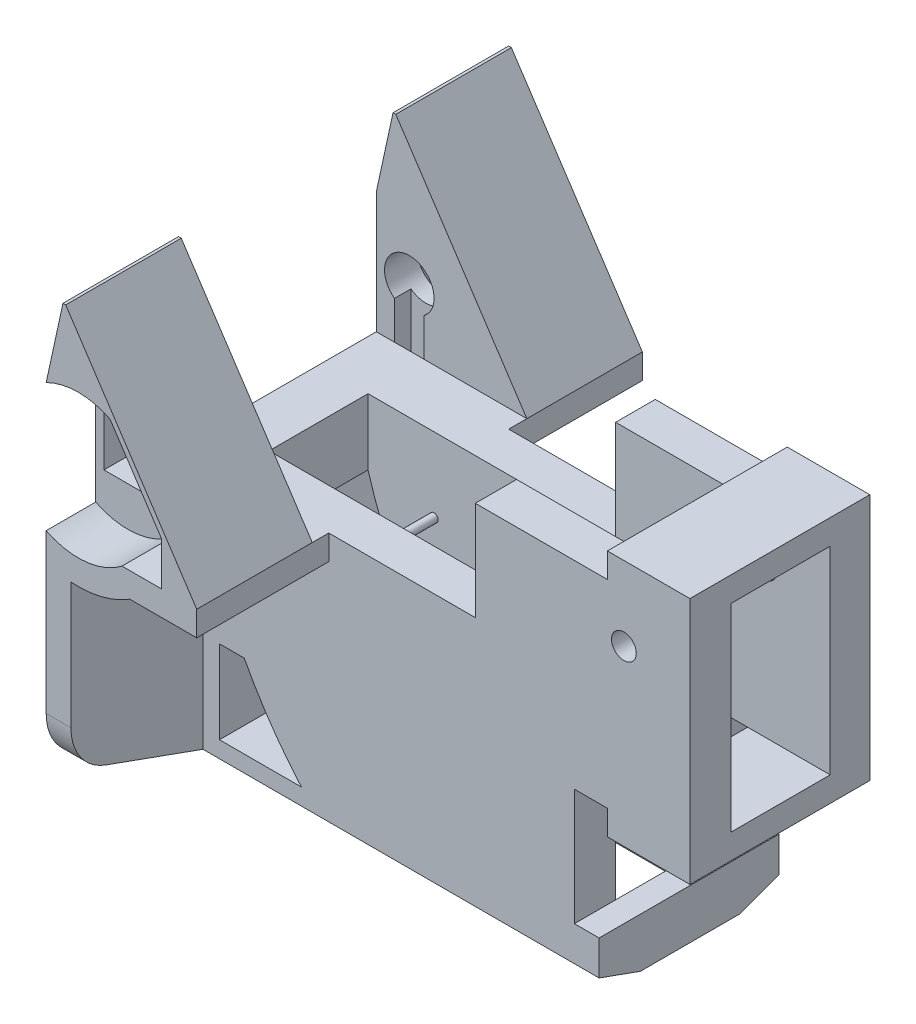
SolidWorks part; units mm, degrees
ref_plane "前视基准面" through (0, 0, 0) normal (0, 0, 1) x (1, 0, 0)
ref_plane "上视基准面" through (0, 0, 0) normal (0, 1, 0) x (1, 0, 0)
ref_plane "右视基准面" through (0, 0, 0) normal (1, 0, 0) x (0, 0, -1)
sketch "草图1" plane through (0, 0, 0) normal (1, 0, 0) x (0, 0, -1)
  line L0 (135, 0) -> (135, -170) construction
  line L1 (0, 0) -> (270, 0)
  line L2 (0, 0) -> (0, -100.2828)
  line L4 (270, 0) -> (270, -100.2828)
  line L5 (38.49, -136.6392) -> (62.3511, -70.3586) construction
  line L6 (21.17, -130.404) -> (127.5448, -168.6989) construction
  line L7 (142.4552, -168.6989) -> (248.83, -130.404) construction
  line L8 (58.2053, -81.8746) -> (-5.8219, -81.8746) construction
  line L9 (58.2053, -81.8746) -> (5.8219, -118.6911) construction
  line L10 (127.5448, -168.6989) -> (21.17, -130.404)
  line L11 (142.4552, -168.6989) -> (248.83, -130.404)
  line L12 (105.5031, -160.7639) -> (135, -78.8281) construction
  line L13 (135, -78.8281) -> (164.4969, -160.7639) construction
  arc A0 (0, -100.2828) -> (21.17, -130.404) centre (32.0136, -100.2828) ccw
  arc A1 (127.5448, -168.6989) -> (142.4552, -168.6989) centre (135, -147.9899) ccw
  arc A2 (270, -100.2828) -> (248.83, -130.404) centre (237.9864, -100.2828) cw
  dimension "D2" = 44.0202
  dimension "D3" = 170
  dimension "D1" = 270
  dimension "D4" = 32.0136
  dimension "D5" = 109.799
  dimension "D6" = 109.799
extrude "凸台-拉伸1" add sketch "草图1" along normal blind 30
sketch "草图2" plane through (30, 0, 0) normal (1, 0, 0) x (0, 0, -1)
  line L0 (135, 0) -> (135, -170) construction
  line L1 (270, 0) -> (0, 0) construction
  line L2 (135, -14.9009) -> (165, -14.9009) construction
  line L3 (165, 0) -> (165, -160.5828)
  line L4 (105, 0) -> (105, -160.5828)
  line L8 (0, 0) -> (0, -100.2828)
  line L9 (21.17, -130.404) -> (127.5448, -168.6989)
  line L10 (142.4552, -168.6989) -> (248.83, -130.404)
  line L11 (270, -100.2828) -> (270, 0)
  line L12 (270, 0) -> (0, 0)
  line L13 (0, 0) -> (0, -100.2828)
  line L14 (21.17, -130.404) -> (127.5448, -168.6989)
  line L15 (142.4552, -168.6989) -> (248.83, -130.404)
  line L16 (270, -100.2828) -> (270, 0)
  line L17 (270, 0) -> (0, 0)
  arc A0 (127.5448, -168.6989) -> (142.4552, -168.6989) centre (135, -147.9899) ccw construction
  arc A4 (0, -100.2828) -> (21.17, -130.404) centre (32.0136, -100.2828) ccw
  arc A5 (127.5448, -168.6989) -> (142.4552, -168.6989) centre (135, -147.9899) ccw
  arc A6 (248.83, -130.404) -> (270, -100.2828) centre (237.9864, -100.2828) ccw
  arc A7 (0, -100.2828) -> (21.17, -130.404) centre (32.0136, -100.2828) ccw
  arc A8 (127.5448, -168.6989) -> (142.4552, -168.6989) centre (135, -147.9899) ccw
  arc A9 (248.83, -130.404) -> (270, -100.2828) centre (237.9864, -100.2828) ccw
  line M12 (0, 0) -> (0, -100.2828)
  arc M13 (0, -100.2828) -> (21.17, -130.404) centre (32.0136, -100.2828) ccw
  line M14 (21.17, -130.404) -> (127.5448, -168.6989)
  line M16 (142.4552, -168.6989) -> (248.83, -130.404)
  arc M17 (248.83, -130.404) -> (270, -100.2828) centre (237.9864, -100.2828) ccw
  line M18 (270, -100.2828) -> (270, 0)
  line M19 (270, 0) -> (0, 0)
  dimension "D1" = 30
  dimension "D2" = 0
extrude "凸台-拉伸2" add sketch "草图2" along normal blind 210 contours L4 M19 M12 M13 M14 | L3 M19 M16 M17 M18
sketch "草图6" plane through (0, 0, -105) normal (0, 0, -1) x (-1, 0, 0)
  line L0 (-71.1167, 0) -> (-71.1167, -409.9146) construction
  line L8 (-30, -160.5828) -> (-30, 0)
  line L9 (-30, 0) -> (-240, 0)
  line L12 (-240, 0) -> (-240, -160.5828)
  line L13 (-240, -160.5828) -> (-30, -160.5828)
  line L15 (-30, -160.5828) -> (-30, 0)
  line L16 (-30, 0) -> (-240, 0)
  line L19 (-240, 0) -> (-240, -160.5828)
  line L20 (-240, -160.5828) -> (-30, -160.5828)
  dimension "D2" = 41.1167
  dimension "D1" = 0
sketch "草图8" plane through (240, 0, 0) normal (1, 0, 0) x (0, 0, -1)
  line L0 (105, 0) -> (105, -160.5828) construction
  line L1 (105, -60) -> (80, -60)
  line L2 (105, -60) -> (105, 60)
  line L3 (105, 60) -> (80, 60)
  line L4 (80, -60) -> (80, 60)
  line L5 (105, -60) -> (80, 60) construction
  line L6 (105, 60) -> (80, -60) construction
  line L7 (135, 0) -> (135, -208.0575) construction
  line L8 (165, 0) -> (105, 0) construction
  line L9 (105, 0) -> (0, 0) construction
  line L10 (165, 60) -> (190, -60) construction
  line L11 (165, -60) -> (190, 60) construction
  line L12 (190, -60) -> (190, 60)
  line L13 (165, 60) -> (190, 60)
  line L14 (165, -60) -> (165, 60)
  line L15 (165, -60) -> (190, -60)
  point P4 (92.5, 0)
  point P17 (177.5, 0)
  dimension "D1" = 25
  dimension "D2" = 60
  dimension "D3" = 60
extrude "凸台-拉伸5" add sketch "草图8" along normal blind 70
sketch "草图9" plane through (240, 0, 0) normal (-1, 0, 0) x (0, 0, 1)
  line L4 (-105, 60) -> (-105, 0)
  line L5 (-105, 0) -> (-80, 0)
  line L6 (-80, 0) -> (-80, 60)
  line L7 (-80, 60) -> (-105, 60)
  line L8 (-105, 60) -> (-105, 0)
  line L9 (-105, 0) -> (-80, 0)
  line L10 (-80, 0) -> (-80, 60)
  line L11 (-80, 60) -> (-105, 60)
  line L12 (-190, 0) -> (-165, 0)
  line L13 (-165, 0) -> (-165, 60)
  line L14 (-165, 60) -> (-190, 60)
  line L15 (-190, 60) -> (-190, 0)
  line L16 (-190, 0) -> (-165, 0)
  line L17 (-165, 0) -> (-165, 60)
  line L18 (-165, 60) -> (-190, 60)
  line L19 (-190, 60) -> (-190, 0)
  dimension "D1" = 0
  dimension "D2" = 0
extrude "凸台-拉伸6" add sketch "草图9" along normal blind 60
sketch "草图10" plane through (0, 0, -80) normal (0, 0, 1) x (1, 0, 0)
  line L0 (240, 0) -> (240, 31.0013) construction
  line L2 (180, 30) -> (270, 30) construction
  line L3 (180, 0) -> (180, 60) construction
  circle A0 centre (270, 30) radius 7.5
  dimension "D2" = 15
  dimension "D1" = 30
extrude "切除-拉伸3" cut sketch "草图10" against normal through all
sketch "草图11" plane through (0, 0, -105) normal (0, 0, -1) x (-1, 0, 0)
  line L0 (0, 0) -> (0, 80.2418) construction
  line L1 (-240, -160.5828) -> (-124.1295, -160.5828) construction
  line L2 (-124.1295, -160.5828) -> (-108.2032, -160.5828) construction
  line L3 (-30, 0) -> (-30, -40) construction
  line L4 (-30, -40) -> (-30, -160.5828)
  line L5 (-30, -160.5828) -> (-108.2032, -160.5828)
  circle A0 centre (-270, 30) radius 240 construction
  arc A1 (-108.2032, -160.5828) -> (-30, -40) centre (-270, 30) ccw
  circle A2 centre (-270, 30) radius 250 construction
  dimension "D1" = 480
  dimension "D2" = 10
extrude "凸台-拉伸7" add sketch "草图11" along normal blind 60
sketch "草图12" plane through (0, 0, -165) normal (0, 0, 1) x (1, 0, 0)
  line L0 (30, 0) -> (240, 0) construction
  line L1 (70, -45) -> (70, 0) construction
  line L4 (30, -160.5828) -> (30, 0) construction
  circle A0 centre (70, -45) radius 2.5
  dimension "D3" = 5
  dimension "D4" = 45
  dimension "D1" = 45
  dimension "D2" = 40
extrude "凸台-拉伸8" add sketch "草图12" along normal through all
sketch "草图13" plane through (0, 0, 0) normal (0, 1, 0) x (1, 0, 0)
  line L0 (0, 270) -> (0, 240.5719) construction
  line L1 (0, 270) -> (0, 0) construction
  line L2 (0, 240.5719) -> (0, 192.1942) construction
sketch "草图14" plane through (0, 0, 0) normal (0, 1, 0) x (1, 0, 0)
  line L0 (0, 250) -> (0, 200)
  line L1 (0, 250) -> (125, 250)
  line L2 (0, 200) -> (125, 200)
  line L3 (125, 250) -> (125, 200)
  line L4 (0, 270) -> (0, 0) construction
  line L5 (240, 270) -> (0, 270) construction
  line L6 (0, 135) -> (52.375, 135) construction
  line L7 (125, 20) -> (125, 70)
  line L8 (0, 70) -> (125, 70)
  line L9 (0, 20) -> (125, 20)
  line L10 (0, 20) -> (0, 70)
  dimension "D1" = 20
  dimension "D2" = 50
  dimension "D3" = 125
extrude "凸台-拉伸9" add sketch "草图14" along normal blind 120
sketch "草图15" plane through (0, 0, -20) normal (0, 0, 1) x (1, 0, 0)
  line L0 (0, 120) -> (0, 0) construction
  line L1 (0, 70) -> (70, 70)
  line L2 (0, 70) -> (0, 0)
  line L3 (0, 0) -> (70, 0)
  line L4 (70, 70) -> (70, 0)
  line L5 (0, 120) -> (125, 120) construction
  dimension "D1" = 70
  dimension "D2" = 70
  dimension "D3" = 50
extrude "切除-拉伸4" cut sketch "草图15" against normal blind 10
sketch "草图16" plane through (0, 0, -30) normal (0, 0, 1) x (1, 0, 0)
  line L0 (0, 35) -> (70, 35) construction
  line L1 (0, 70) -> (0, 0) construction
  line L2 (70, 0) -> (70, 70) construction
  line L3 (0, 35) -> (35, 35) construction
  line L4 (35, 70) -> (35, 0) construction
  line L5 (35, 35) -> (35, 15)
  line L6 (70, 70) -> (0, 70) construction
  line L7 (0, 35) -> (35, 35) construction
  line L8 (0, 0) -> (70, 0) construction
  line L9 (35, 35) -> (35, 55) construction
  line L10 (35, 55) -> (5, 55) construction
  line L11 (35, 35) -> (35, 55)
  line L12 (35, 55) -> (5, 55)
  line L13 (5, 55) -> (5, 15)
  line L14 (35, 15) -> (5, 15)
  point P21 (5, 35)
  dimension "D1" = 35
  dimension "D2" = 20
  dimension "D3" = 30
extrude "切除-拉伸5" cut sketch "草图16" against normal blind 20 contours L14 L5 L11 L12 L13
sketch "草图17" plane through (0, 0, -30) normal (0, 0, 1) x (1, 0, 0)
  line L0 (35, 35) -> (19.5, 34.5) construction
  line L1 (35, 55) -> (35, 15) construction
  circle A0 centre (19.5, 34.5) radius 43.4713
extrude "切除-拉伸6" cut sketch "草图17" along normal through all
sketch "草图18" plane through (0, 0, -20) normal (0, 0, 1) x (1, 0, 0)
  line L0 (0, 73.3523) -> (11.8199, 120) construction
  line L1 (0, 73.3523) -> (0, -4.3523) construction
  line L2 (0, 120) -> (125, 120) construction
  line L3 (11.8199, 120) -> (62.5, 43.3973) construction
  line L4 (62.5, 43.3973) -> (91.2115, 0) construction
  line L5 (11.8199, 120) -> (91.2115, 0)
  line L6 (91.2115, 0) -> (87.3179, 0)
  line L7 (70, 0) -> (125, 0) construction
  line L8 (87.3179, 0) -> (10.7417, 115.7446)
  line L9 (10.7417, 115.7446) -> (11.8199, 120)
  arc A0 (44.5899, 70) -> (0, 73.3523) centre (19.5, 34.5) ccw construction
extrude "凸台-拉伸10" add sketch "草图18" along normal blind 20
sketch "草图19" plane through (0, 0, -20) normal (0, 0, 1) x (1, 0, 0)
  line L0 (10.856, 115.5717) -> (11.8199, 120)
  line L1 (10.7417, 115.7446) -> (87.3179, 0) construction
  line L2 (11.8199, 120) -> (10.7417, 115.7446) construction
  line L3 (11.8199, 120) -> (125, 120) construction
  line L4 (11.8199, 120) -> (0, 65.6972)
  line L5 (0, 73.3523) -> (0, -4.3523) construction
  line L6 (0, 65.6972) -> (0, 73.3523)
  line L7 (0, 120) -> (0, 73.3523) construction
  line L8 (0, 73.3523) -> (10.1537, 120)
  line L9 (0, 120) -> (11.8199, 120) construction
  line L10 (10.1537, 120) -> (11.8199, 120)
  line L11 (10.1537, 120) -> (11.8199, 120)
  line M2 (38.6846, 73.509) -> (10.7417, 115.7446)
  line M3 (10.7417, 115.7446) -> (11.8199, 120)
  line M4 (11.8199, 120) -> (0, 120)
  arc M6 (0, 73.3523) -> (38.6846, 73.509) centre (19.5, 34.5) cw
extrude "凸台-拉伸11" add sketch "草图19" along normal blind 20 contours L8 L4 M6 M2 M3 M4
sketch "草图20" plane through (0, 0, -20) normal (0, 0, 1) x (1, 0, 0)
  line L3 (0, 120) -> (0, 73.3523)
  line L4 (0, 73.3523) -> (10.1537, 120)
  line L5 (10.1537, 120) -> (0, 120)
  line L6 (0, 120) -> (0, 73.3523)
  line L7 (0, 73.3523) -> (10.1537, 120)
  line L8 (10.1537, 120) -> (0, 120)
  dimension "D1" = 0
extrude "切除-拉伸7" cut sketch "草图20" against normal through all
sketch "草图22" plane through (0, 0, -20) normal (0, 0, 1) x (1, 0, 0)
  line L0 (44.8997, 70) -> (70, 32.0611)
  line L7 (70, 32.0611) -> (91.2115, 0)
  line L8 (91.2115, 0) -> (125, 0)
  line L9 (125, 0) -> (125, 120)
  line L10 (125, 120) -> (11.8199, 120)
  line L11 (11.8199, 120) -> (44.8997, 70)
  line L12 (44.8997, 70) -> (70, 70)
  line L13 (70, 70) -> (70, 32.0611)
  line L14 (70, 32.0611) -> (91.2115, 0)
  line L15 (91.2115, 0) -> (125, 0)
  line L16 (125, 0) -> (125, 120)
  line L17 (125, 120) -> (11.8199, 120)
  line L18 (11.8199, 120) -> (44.8997, 70)
  dimension "D1" = 0
extrude "切除-拉伸8" cut sketch "草图22" against normal through all
sketch "草图23" plane through (0, 0, 0) normal (0, 0, 1) x (1, 0, 0)
  line L0 (87.3179, 0) -> (91.2115, 0)
  line L10 (0, -4.3523) -> (0, -100.2828)
  line L11 (0, -100.2828) -> (240, -100.2828)
  line L12 (240, -100.2828) -> (240, 0)
  line L13 (240, 0) -> (91.2115, 0)
  line L14 (91.2115, 0) -> (11.8199, 120)
  line L15 (11.8199, 120) -> (10.1537, 120)
  line L16 (10.1537, 120) -> (0, 73.3523)
  line L17 (1.8573, 74.2302) -> (10.856, 115.5717)
  line L18 (10.856, 115.5717) -> (87.3179, 0)
  line L19 (87.3179, 0) -> (45.9481, 0)
  line L20 (0, -4.3523) -> (0, -100.2828)
  line L21 (0, -100.2828) -> (240, -100.2828)
  line L22 (240, -100.2828) -> (240, 0)
  line L23 (240, 0) -> (91.2115, 0)
  line L24 (91.2115, 0) -> (11.8199, 120)
  line L25 (11.8199, 120) -> (10.1537, 120)
  line L26 (10.1537, 120) -> (0, 73.3523)
  line L27 (1.8573, 74.2302) -> (10.856, 115.5717)
  line L28 (10.856, 115.5717) -> (87.3179, 0)
  line L29 (87.3179, 0) -> (45.9481, 0)
  arc A2 (0, -4.3523) -> (45.9481, 0) centre (19.5, 34.5) ccw
  arc A3 (1.8573, 74.2302) -> (0, 73.3523) centre (19.5, 34.5) ccw
  arc A4 (0, -4.3523) -> (45.9481, 0) centre (19.5, 34.5) ccw
  arc A5 (1.8573, 74.2302) -> (0, 73.3523) centre (19.5, 34.5) ccw
  line M18 (91.2115, 0) -> (11.8199, 120)
  line M19 (11.8199, 120) -> (10.1537, 120)
  line M20 (10.1537, 120) -> (0, 73.3523)
  arc M21 (0, 73.3523) -> (1.8573, 74.2302) centre (19.5, 34.5) cw
  line M22 (1.8573, 74.2302) -> (10.856, 115.5717)
  line M23 (10.856, 115.5717) -> (87.3179, 0)
  dimension "D1" = 0
extrude "凸台-拉伸19" add sketch "草图23" against normal up to next contours L0 M23 M18 M19 M20 M21 M22
sketch "草图24" plane through (0, 0, -20) normal (0, 0, 1) x (1, 0, 0)
  line L3 (87.3179, 0) -> (70, 26.1759)
  line L4 (70, 26.1759) -> (70, 0)
  line L5 (70, 0) -> (87.3179, 0)
  line L6 (87.3179, 0) -> (70, 26.1759)
  line L7 (70, 26.1759) -> (70, 0)
  line L8 (70, 0) -> (87.3179, 0)
  dimension "D1" = 0
extrude "凸台-拉伸20" add sketch "草图24" along normal up to vertex (20 mm away)
sketch "草图25" plane through (0, 0, -20) normal (0, 0, 1) x (1, 0, 0)
  line L2 (38.6846, 73.509) -> (10.856, 115.5717)
  line L3 (10.856, 115.5717) -> (1.8573, 74.2302)
  line L4 (38.6846, 73.509) -> (10.856, 115.5717)
  line L5 (10.856, 115.5717) -> (1.8573, 74.2302)
  arc A1 (38.6846, 73.509) -> (1.8573, 74.2302) centre (19.5, 34.5) ccw
  arc A2 (38.6846, 73.509) -> (1.8573, 74.2302) centre (19.5, 34.5) ccw
  dimension "D1" = 0
extrude "凸台-拉伸21" add sketch "草图25" along normal blind 20
sketch "草图26" plane through (0, 0, -250) normal (0, 0, -1) x (-1, 0, 0)
  line L10 (-70, 26.1759) -> (-38.6846, 73.509)
  line L11 (-70, 0) -> (-70, 26.1759)
  line L12 (-45.9481, 0) -> (-70, 0)
  line L13 (0, -100.2828) -> (0, -4.3523)
  line L14 (-240, -100.2828) -> (0, -100.2828)
  line L15 (-240, 0) -> (-240, -100.2828)
  line L16 (-91.2115, 0) -> (-240, 0)
  line L17 (-11.8199, 120) -> (-91.2115, 0)
  line L18 (-10.1537, 120) -> (-11.8199, 120)
  line L19 (0, 73.3523) -> (-10.1537, 120)
  line L20 (-70, 26.1759) -> (-38.6846, 73.509)
  line L21 (-70, 0) -> (-70, 26.1759)
  line L22 (-45.9481, 0) -> (-70, 0)
  line L23 (0, -100.2828) -> (0, -4.3523)
  line L24 (-240, -100.2828) -> (0, -100.2828)
  line L25 (-240, 0) -> (-240, -100.2828)
  line L26 (-91.2115, 0) -> (-240, 0)
  line L27 (-11.8199, 120) -> (-91.2115, 0)
  line L28 (-10.1537, 120) -> (-11.8199, 120)
  line L29 (0, 73.3523) -> (-10.1537, 120)
  arc A2 (0, 73.3523) -> (-38.6846, 73.509) centre (-19.5, 34.5) ccw
  arc A3 (-45.9481, 0) -> (0, -4.3523) centre (-19.5, 34.5) ccw
  arc A4 (0, 73.3523) -> (-38.6846, 73.509) centre (-19.5, 34.5) ccw
  arc A5 (-45.9481, 0) -> (0, -4.3523) centre (-19.5, 34.5) ccw
  dimension "D1" = 0
extrude "凸台-拉伸22" add sketch "草图26" along normal blind 20
sketch "草图27" plane through (0, 0, -270) normal (0, 0, -1) x (-1, 0, 0)
  line L4 (-38.6846, 73.509) -> (-70, 26.1759)
  line L5 (0, -4.3523) -> (0, 73.3523)
  line L6 (-70, 0) -> (-45.9481, 0)
  line L7 (-70, 26.1759) -> (-70, 0)
  line L8 (-38.6846, 73.509) -> (-70, 26.1759)
  line L9 (0, -4.3523) -> (0, 73.3523)
  line L10 (-70, 0) -> (-45.9481, 0)
  line L11 (-70, 26.1759) -> (-70, 0)
  arc A2 (0, 73.3523) -> (-38.6846, 73.509) centre (-19.5, 34.5) ccw
  arc A3 (-45.9481, 0) -> (0, -4.3523) centre (-19.5, 34.5) ccw
  arc A4 (0, 73.3523) -> (-38.6846, 73.509) centre (-19.5, 34.5) ccw
  arc A5 (-45.9481, 0) -> (0, -4.3523) centre (-19.5, 34.5) ccw
  dimension "D1" = 0
extrude "切除-拉伸9" cut sketch "草图27" against normal blind 30
sketch "草图29" plane through (0, 0, -70) normal (0, 0, -1) x (-1, 0, 0)
  line L0 (-5, 55) -> (-35, 15) construction
  line L1 (-5, 15) -> (-35, 55) construction
  line L4 (-35, 15) -> (-5, 15)
  line L5 (-35, 55) -> (-35, 15)
  line L6 (-5, 55) -> (-35, 55)
  line L7 (-5, 15) -> (-5, 55)
  line L8 (-35, 15) -> (-5, 15) construction
  line L9 (-35, 55) -> (-35, 15) construction
  line L10 (-5, 55) -> (-35, 55) construction
  line L11 (-5, 15) -> (-5, 55) construction
  circle A0 centre (-20, 35) radius 15
  dimension "D2" = 30
  dimension "D1" = 0
extrude "切除-拉伸11" cut sketch "草图29" against normal through all both and the other way through all
sketch "草图30" plane through (30, 0, 0) normal (1, 0, 0) x (0, 0, -1)
  line L3 (142.4552, -168.6989) -> (165, -160.5828)
  line L4 (165, -160.5828) -> (105, -160.5828)
  line L5 (105, -160.5828) -> (127.5448, -168.6989)
  line L6 (142.4552, -168.6989) -> (165, -160.5828)
  line L7 (165, -160.5828) -> (105, -160.5828)
  line L8 (105, -160.5828) -> (127.5448, -168.6989)
  arc A1 (127.5448, -168.6989) -> (142.4552, -168.6989) centre (135, -147.9899) ccw
  arc A2 (127.5448, -168.6989) -> (142.4552, -168.6989) centre (135, -147.9899) ccw
  dimension "D1" = 0
extrude "凸台-拉伸23" add sketch "草图30" along normal up to vertex (78.2032 mm away) up to point (108.2032, -160.5828, -165)
sketch "草图33" plane through (0, 0, -240) normal (0, 0, -1) x (-1, 0, 0)
  line L0 (-35, 15) -> (-5, 15) construction
  line L1 (-35, 55) -> (-35, 15) construction
  line L2 (-35, 55) -> (-5, 55) construction
  line L3 (-5, 55) -> (-5, 15) construction
  line L4 (-35, 15) -> (-5, 15)
  line L5 (-35, 55) -> (-35, 15)
  line L6 (-35, 55) -> (-5, 55)
  line L7 (-5, 55) -> (-5, 15)
extrude "切除-拉伸14" cut sketch "草图33" against normal blind 20
sketch "草图34" plane through (0, 0, -200) normal (0, 0, 1) x (1, 0, 0)
  line L0 (20, 50) -> (20, 2.4606) construction
  line L1 (11, 0) -> (11, 35.3006)
  line L2 (11, 0) -> (29, 0)
  line L3 (11, 35.3006) -> (29, 35.3006)
  line L4 (29, 0) -> (29, 35.3006)
  line L5 (11, 0) -> (29, 35.3006) construction
  line L6 (11, 35.3006) -> (29, 0) construction
  line L7 (0, 0) -> (91.2115, 0) construction
  arc A0 (35, 35) -> (5, 35) centre (20, 35) ccw construction
  point P7 (20, 17.6503)
  dimension "D1" = 18
extrude "切除-拉伸15" cut sketch "草图34" against normal blind 10
sketch "草图35" plane through (0, 0, -70) normal (0, 0, -1) x (-1, 0, 0)
  line L3 (-11, 0) -> (-11, 23)
  line L4 (-29, 0) -> (-11, 0)
  line L5 (-29, 23) -> (-29, 0)
  line L6 (-11, 0) -> (-11, 23)
  line L7 (-29, 0) -> (-11, 0)
  line L8 (-29, 23) -> (-29, 0)
  arc A1 (-29, 23) -> (-11, 23) centre (-20, 35) ccw
  arc A2 (-29, 23) -> (-11, 23) centre (-20, 35) ccw
  dimension "D1" = 0
extrude "切除-拉伸16" cut sketch "草图35" against normal blind 10
sketch "草图36" plane through (0, 0, 0) normal (-1, 0, 0) x (0, 0, 1)
  line L0 (-235.6917, -100.008) -> (-211.6417, -100.008) construction
  line L1 (-135, -147.9899) -> (-135, -104.794) construction
  line L2 (-34.3083, -100.008) -> (-58.3583, -100.008) construction
  circle A0 centre (-235.6917, -100.008) radius 15.9
  circle A1 centre (-34.3083, -100.008) radius 15.9
  ellipse E0 centre (-235.6917, -100.008) end of major axis (-211.6417, -100.008) minor radius 15.9
  ellipse E1 centre (-34.3083, -100.008) end of major axis (-58.3583, -100.008) minor radius 15.9
  dimension "D2" = 31.8
  dimension "D1" = 24.05
extrude "切除-拉伸17" cut sketch "草图36" against normal blind 4 contours A0 E0 | A0 | A0 E0 | E1 A1 | A1 | E1 A1
sketch "草图37" plane through (0, 0, 0) normal (0, 1, 0) x (1, 0, 0)
  line L0 (108.2032, 135) -> (337.5794, 135) construction
  line L1 (240, 80) -> (91.2115, 80)
  line L2 (240, 80) -> (240, 0)
  line L3 (240, 0) -> (91.2115, 0)
  line L4 (91.2115, 80) -> (91.2115, 0)
  line L5 (108.2032, 165) -> (108.2032, 105) construction
  line L6 (91.2115, 190) -> (91.2115, 270)
  line L7 (240, 270) -> (91.2115, 270)
  line L8 (240, 190) -> (240, 270)
  line L9 (240, 190) -> (91.2115, 190)
extrude "切除-拉伸18" cut sketch "草图37" against normal through all
sketch "草图38" plane through (0, 0, 0) normal (0, 0, 1) x (1, 0, 0)
  line L1 (70, -15) -> (76.2115, -15)
  line L2 (76.2115, -85.2828) -> (76.2115, -15)
  line L3 (15, -85.2828) -> (76.2115, -85.2828)
  line L4 (15, -23.7978) -> (15, -85.2828)
  line L5 (70, -15) -> (50.623, -15)
  line L6 (76.2115, -15) -> (91.2115, -15)
  line L7 (91.2115, -100.2828) -> (91.2115, 0) construction
  line L8 (91.2115, -15) -> (91.2115, -100.2828)
  line L9 (91.2115, -100.2828) -> (0, -100.2828) construction
  line L10 (91.2115, -100.2828) -> (15, -100.2828)
  line L11 (15, -100.2828) -> (15, -85.2828)
  line L12 (91.2115, -15) -> (91.2115, -100.2828)
  line L14 (91.2115, -151.5828) -> (91.2115, 0) construction
  line L15 (91.2115, -151.5828) -> (91.2115, 0)
  line L17 (91.2115, -151.5828) -> (15, -151.5828)
  line L18 (91.2115, -151.5828) -> (91.2115, -100.2828)
  line L19 (91.2115, -100.2828) -> (15, -100.2828)
  line L20 (15, -151.5828) -> (15, -100.2828)
  arc A0 (15, -23.7978) -> (50.623, -15) centre (19.5, 34.5) ccw
  line M12 (0, -100.2828) -> (91.2115, -100.2828)
  line M13 (91.2115, -100.2828) -> (91.2115, 0)
extrude "切除-拉伸20" cut sketch "草图38" against normal blind 80 contours L20 L17 L15 M12 | L11 L6 L2 L3 M12 M13 | A0 L4 L3 L2 L1 L5
sketch "草图39" plane through (0, 0, -270) normal (0, 0, -1) x (-1, 0, 0)
  line L10 (-180, 60) -> (-310, 60)
  line L11 (-180, 0) -> (-180, 60)
  line L12 (-91.2115, 0) -> (-180, 0)
  line L13 (-91.2115, -15) -> (-91.2115, 0)
  line L14 (-50.623, -15) -> (-91.2115, -15)
  line L15 (-15, -151.5828) -> (-15, -23.7978)
  line L16 (-240, -151.5828) -> (-15, -151.5828)
  line L17 (-240, -60) -> (-240, -151.5828)
  line L18 (-310, -60) -> (-240, -60)
  line L19 (-310, 60) -> (-310, -60)
  line L20 (-180, 60) -> (-310, 60)
  line L21 (-180, 0) -> (-180, 60)
  line L22 (-91.2115, 0) -> (-180, 0)
  line L23 (-91.2115, -15) -> (-91.2115, 0)
  line L24 (-50.623, -15) -> (-91.2115, -15)
  line L25 (-15, -151.5828) -> (-15, -23.7978)
  line L26 (-240, -151.5828) -> (-15, -151.5828)
  line L27 (-240, -60) -> (-240, -151.5828)
  line L28 (-310, -60) -> (-240, -60)
  line L29 (-310, 60) -> (-310, -60)
  arc A1 (-50.623, -15) -> (-15, -23.7978) centre (-19.5, 34.5) ccw
  arc A2 (-50.623, -15) -> (-15, -23.7978) centre (-19.5, 34.5) ccw
  dimension "D1" = 0
extrude "切除-拉伸21" cut sketch "草图39" against normal blind 81
sketch "草图40" plane through (0, 0, -80) normal (0, 0, 1) x (1, 0, 0)
  line L0 (98.1638, -151.5828) -> (30, -151.5828) construction
  line L1 (240, -151.5828) -> (15, -151.5828) construction
  line L2 (30, -151.5828) -> (30, -40) construction
  line L3 (74.6558, -141.5828) -> (40, -141.5828)
  line L4 (40, -141.5828) -> (40, -91.2436)
  arc A1 (30, -40) -> (108.2032, -160.5828) centre (270, 30) ccw construction
  arc A2 (30, -40) -> (98.1638, -151.5828) centre (270, 30) ccw construction
  arc A3 (40, -91.2436) -> (74.6558, -141.5828) centre (270, 30) ccw
  dimension "D1" = 10
extrude "切除-拉伸22" cut sketch "草图40" against normal through all
sketch "草图41" plane through (0, 0, 0) normal (0, 1, 0) x (1, 0, 0)
  line L0 (29, 60) -> (11, 60) construction
  line L1 (29, 60) -> (11, 60)
  line L2 (29, 60) -> (29, 70) construction
  line L3 (29, 60) -> (29, 70)
  line L4 (11, 60) -> (11, 70) construction
  line L5 (11, 60) -> (11, 70)
  line L6 (11, 70) -> (29, 70)
  line L7 (0, 135) -> (128.1299, 135) construction
  line L8 (0, 200) -> (0, 70) construction
  line L9 (11, 200) -> (29, 200)
  line L10 (11, 210) -> (11, 200)
  line L11 (29, 210) -> (29, 200)
  line L12 (29, 210) -> (11, 210)
extrude "切除-拉伸23" cut sketch "草图41" against normal blind 60
sketch "草图44" plane through (0, 60, 0) normal (0, 1, 0) x (1, 0, 0)
  line L0 (310, 80) -> (180, 80) construction
  line L1 (310, 189) -> (260, 189)
  line L2 (310, 189) -> (310, 80)
  line L3 (310, 80) -> (260, 80)
  line L4 (260, 189) -> (260, 80)
  dimension "D1" = 50
extrude "凸台-拉伸26" add sketch "草图44" along normal blind 15
sketch "草图45" plane through (0, -60, 0) normal (0, -1, 0) x (1, 0, 0)
  line L0 (310, -189) -> (240, -189) construction
  line L1 (310, -80) -> (260, -80)
  line L2 (310, -80) -> (310, -189)
  line L3 (310, -189) -> (260, -189)
  line L4 (260, -80) -> (260, -189)
  dimension "D1" = 50
extrude "凸台-拉伸27" add sketch "草图45" along normal blind 15
sketch "草图46" plane through (240, 0, 0) normal (1, 0, 0) x (0, 0, -1)
  line L0 (80, -151.5828) -> (105, -160.5828) construction
  line L1 (80, -151.5828) -> (105, -160.5828)
  line L2 (165, -160.5828) -> (190, -151.5828) construction
  line L3 (165, -160.5828) -> (189, -151.9428)
  line L4 (105, -160.5828) -> (165, -160.5828)
  line L5 (189, -60) -> (189, -151.5828) construction
  line L7 (80, -151.5828) -> (80, -130.5828)
  line L8 (80, -130.5828) -> (189, -130.5828)
  line L10 (189, -130.5828) -> (189, -151.9428)
  dimension "D2" = 30
extrude "凸台-拉伸28" add sketch "草图46" along normal blind 15
sketch "草图47" plane through (0, 0, -189) normal (0, 0, -1) x (-1, 0, 0)
  line L1 (-40, -91.2436) -> (-25, -91.2436)
  line L2 (-40, -91.2436) -> (-40, -141.5828)
  line L3 (-40, -141.5828) -> (-25, -141.5828)
  line L4 (-25, -91.2436) -> (-25, -141.5828)
  arc A0 (-74.6558, -141.5828) -> (-40, -91.2436) centre (-270, 30) ccw construction
  arc A1 (-74.6558, -141.5828) -> (-40, -91.2436) centre (-270, 30) ccw construction
  arc A2 (-108.2032, -160.5828) -> (-30, -40) centre (-270, 30) ccw construction
  arc A3 (-108.2032, -160.5828) -> (-30, -40) centre (-270, 30) ccw construction
  dimension "D1" = 15
extrude "切除-拉伸24" cut sketch "草图47" against normal up to surface (109 mm away) up to face at (51.0572, -125.1437, -80)
